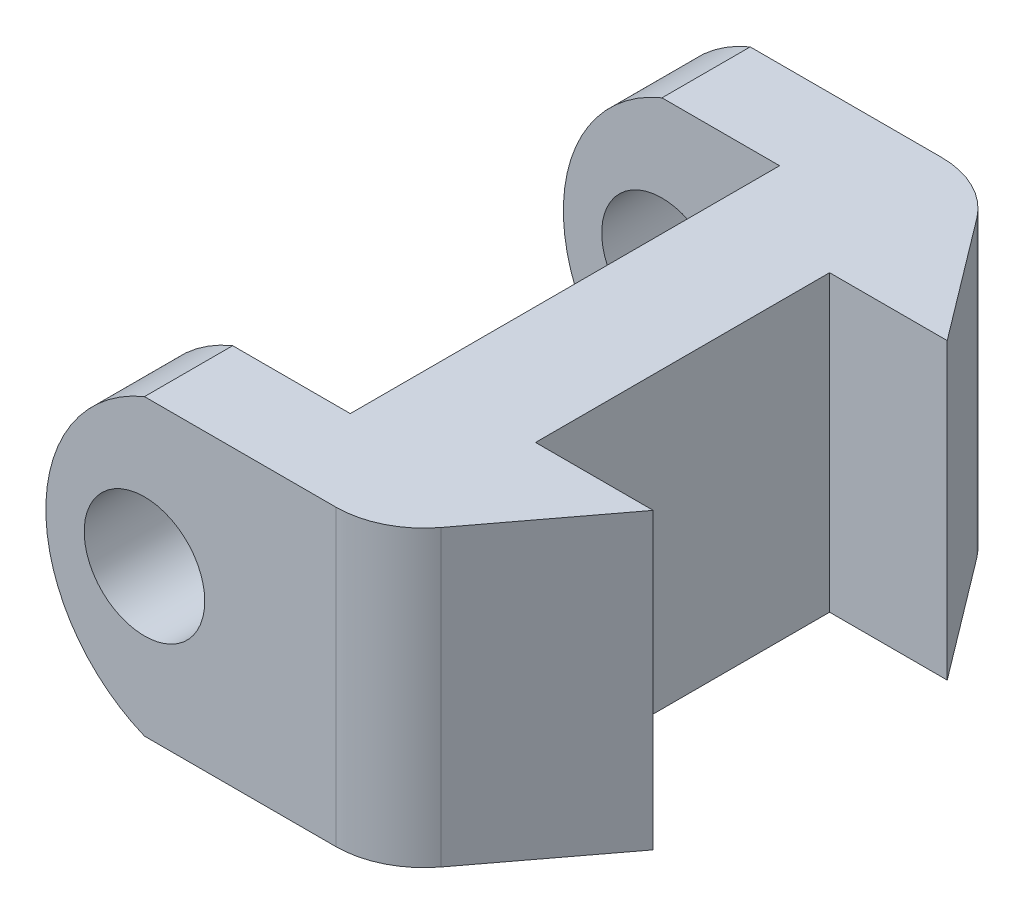
SolidWorks part; units mm, degrees
ref_plane "Front Plane" through (0, 0, 0) normal (0, 0, 1) x (1, 0, 0)
ref_plane "Top Plane" through (0, 0, 0) normal (0, 1, 0) x (1, 0, 0)
ref_plane "Right Plane" through (0, 0, 0) normal (1, 0, 0) x (0, 0, -1)
sketch "Sketch1" plane through (0, 0, 0) normal (0, 1, 0) x (1, 0, 0)
  line L1 (6, -10.3) -> (-6, -10.3)
  line L2 (6, -10.3) -> (6, 10.3)
  line L3 (6, 10.3) -> (-6, 10.3)
  line L4 (-6, -10.3) -> (-6, 10.3)
  line L5 (6, -10.3) -> (-6, 10.3) construction
  line L6 (6, 10.3) -> (-6, -10.3) construction
  line L7 (2, -7.3) -> (-6, -7.3)
  line L8 (2, -7.3) -> (2, 7.3)
  line L9 (2, 7.3) -> (-6, 7.3)
  line L10 (-6, -7.3) -> (-6, 7.3)
  line L11 (2, -7.3) -> (-6, 7.3) construction
  line L12 (2, 7.3) -> (-6, -7.3) construction
  point P0 (0, 0)
  point P6 (-2, 0)
  dimension "D1" = 14.6
  dimension "D2" = 4
  dimension "D3" = 12
  dimension "D4" = 3
extrude "Boss-Extrude1" add sketch "Sketch1" along normal blind 10 contours L9 L8 L7 L4 L1 L2 L3
sketch "Sketch2" plane through (0, 0, -7.3) normal (0, 0, 1) x (1, 0, 0)
  line L0 (2, 0) -> (-6, 10)
  circle A0 centre (-2, 5) radius 2.05
  dimension "D1" = 4.1
extrude "Cut-Extrude1" cut sketch "Sketch2" against normal through all both and the other way through all contours L0 A0 | L0 A0
sketch "Sketch3" plane through (0, 10, 0) normal (0, 1, 0) x (1, 0, 0)
  line L0 (6, 10.3) -> (10, 5)
  line L1 (10, 5) -> (10, -5)
  line L2 (10, -5) -> (6, -10.3)
  line L3 (10, -5) -> (6, -5)
  line L4 (6, -10.3) -> (6, 10.3) construction
  line L5 (10, 5) -> (6, 5)
  point P9 (10, 0)
  line M8 (6, -10.3) -> (6, 10.3)
  dimension "D1" = 10
  dimension "D2" = 4
extrude "Boss-Extrude2" add sketch "Sketch3" against normal up to surface (10 mm away) contours L5 L0 M8 | L2 L3 M8 up to face at (-1, 0, 0)
fillet "Fillet1" radius 3 2 edges at (6, 5, -10.3) (6, 5, 10.3)
sketch "Sketch4" plane through (0, 0, -10.3) normal (0, 0, -1) x (-1, 0, 0)
  line L0 (-4.5056, 10) -> (6, 10) construction
  line L1 (-4.5056, 0) -> (6, 0) construction
  line L2 (2, 10) -> (6, 10)
  line L3 (6, 10) -> (6, 0)
  line L4 (6, 0) -> (2, 0)
  arc A0 (2, 10) -> (2, 0) centre (-0.05, 5) cw
  circle A1 centre (2, 5) radius 2.05 construction
extrude "Cut-Extrude2" cut sketch "Sketch4" against normal through all both and the other way through all
